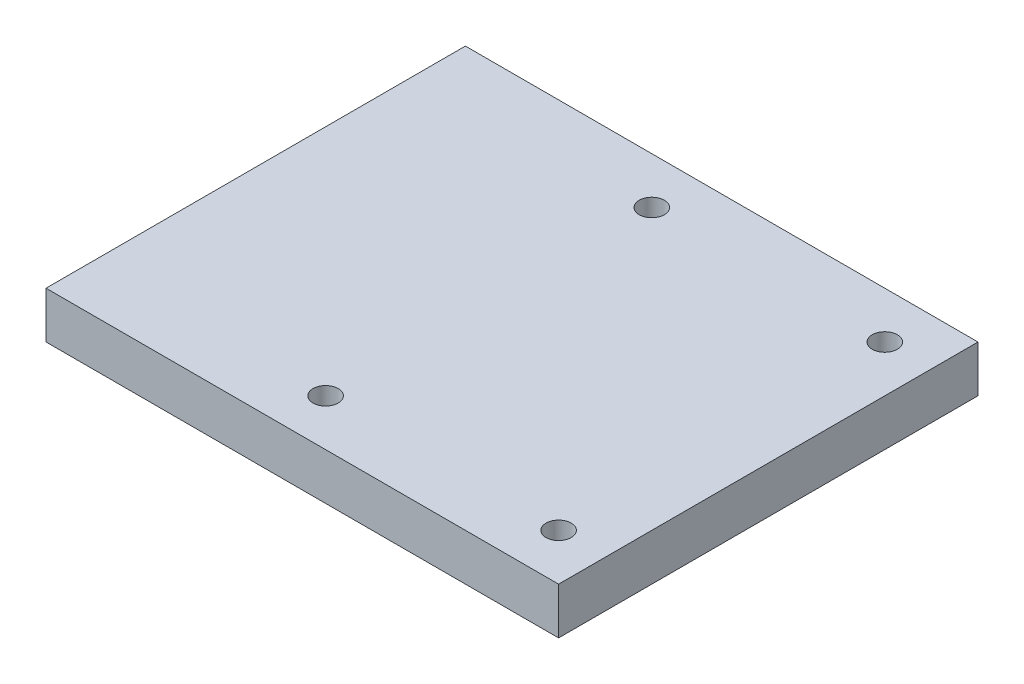
SolidWorks part; units mm, degrees
material "6061 Alloy"
ref_plane "Front Plane" through (0, 0, 0) normal (0, 0, 1) x (1, 0, 0)
ref_plane "Top Plane" through (0, 0, 0) normal (0, 1, 0) x (1, 0, 0)
ref_plane "Right Plane" through (0, 0, 0) normal (1, 0, 0) x (0, 0, -1)
sketch "Sketch1" plane through (0, 0, 0) normal (0, 1, 0) x (1, 0, 0)
  line L1 (-69.85, 57.15) -> (69.85, 57.15)
  line L2 (-69.85, 57.15) -> (-69.85, -57.15)
  line L3 (-69.85, -57.15) -> (69.85, -57.15)
  line L4 (69.85, 57.15) -> (69.85, -57.15)
  line L5 (-69.85, 57.15) -> (69.85, -57.15) construction
  line L6 (-69.85, -57.15) -> (69.85, 57.15) construction
  point P0 (0, 0)
  dimension "D1" = 114.3
  dimension "D2" = 139.7
extrude "Boss-Extrude1" add sketch "Sketch1" along normal blind 12.7
sketch "Sketch3" plane through (0, 0, 0) normal (0, -1, 0) x (1, 0, 0)
  line L0 (25.4, 0) -> (25.4, -20.7585) construction
  line L1 (0, 0) -> (-13.1006, 0) construction
  line L3 (-69.85, 57.15) -> (69.85, 57.15) construction
  line L4 (69.85, -57.15) -> (-69.85, -57.15) construction
  line L5 (69.85, 57.15) -> (69.85, -57.15) construction
  line L6 (69.85, 57.15) -> (69.85, -57.15) construction
  circle A0 centre (-6.35, 44.45) radius 3.429
  circle A1 centre (-6.35, -44.45) radius 3.429
  circle A2 centre (57.15, 44.45) radius 3.429
  circle A3 centre (57.15, -44.45) radius 3.429
  dimension "D1" = 76.2
  dimension "D4" = 12.7
  dimension "D2" = 12.7
  dimension "D3" = 12.7
extrude "Cut-Extrude2" cut sketch "Sketch3" against normal up to next
sketch "Sketch4" plane through (0, 0, 0) normal (0, -1, 0) x (1, 0, 0)
  line L0 (-69.85, -57.15) -> (-69.85, 57.15) construction
  circle A0 centre (-53.975, 0) radius 12.7
  dimension "D1" = 15.875
extrude "Cut-Extrude3" cut sketch "Sketch4" against normal blind 7.874
